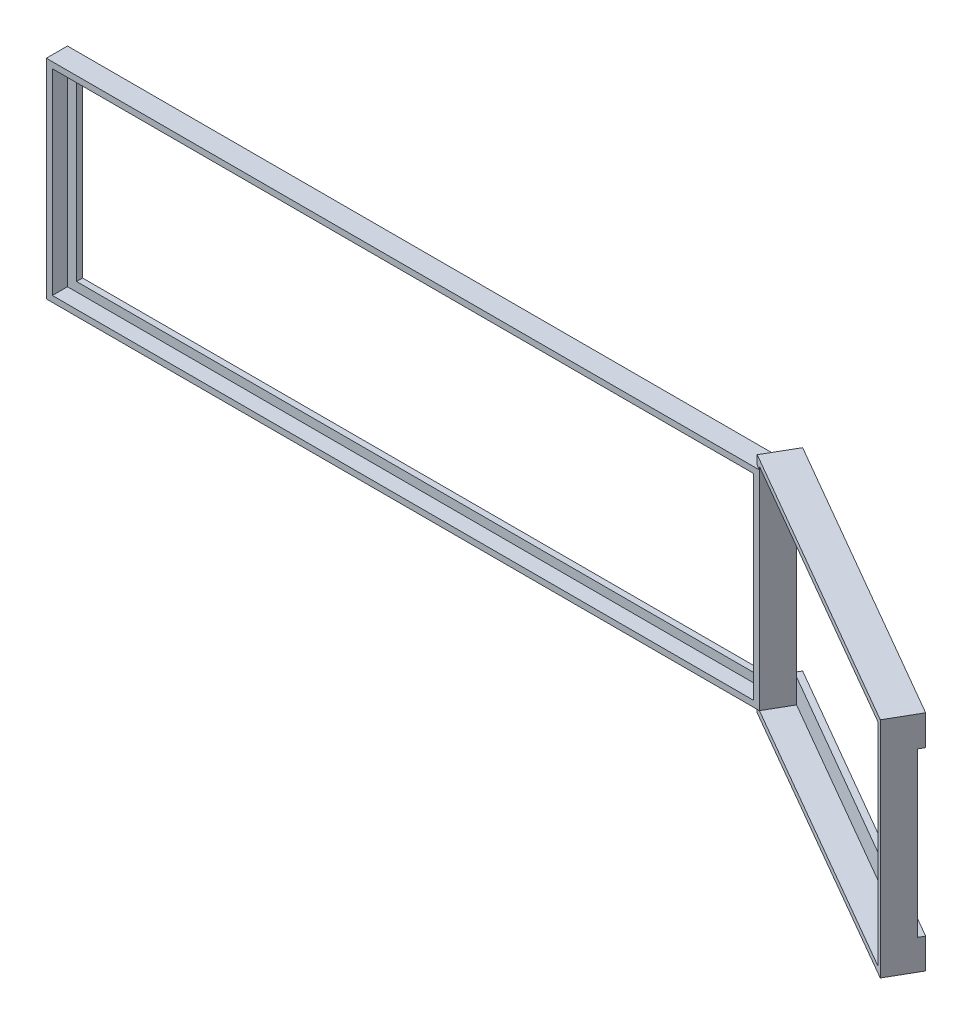
SolidWorks part; units mm, degrees
ref_plane "Front Plane" through (0, 0, 0) normal (0, 0, 1) x (1, 0, 0)
ref_plane "Top Plane" through (0, 0, 0) normal (0, 1, 0) x (1, 0, 0)
ref_plane "Right Plane" through (0, 0, 0) normal (1, 0, 0) x (0, 0, -1)
sketch "Sketch1" plane through (0, 0, 0) normal (0, 0, 1) x (1, 0, 0)
  line L0 (-118, 34.5) -> (-118, -34.5)
  line L1 (-116, 32.5) -> (116, 32.5)
  line L2 (-116, 32.5) -> (-116, -32.5)
  line L3 (-116, -32.5) -> (116, -32.5)
  line L4 (116, 32.5) -> (116, -32.5)
  line L5 (-116, 32.5) -> (116, -32.5) construction
  line L6 (-116, -32.5) -> (116, 32.5) construction
  line L7 (-118, -34.5) -> (118, -34.5)
  line L8 (118, 34.5) -> (118, -34.5)
  line L9 (-118, 34.5) -> (118, 34.5)
  point P0 (0, 0)
  dimension "D1" = 232
  dimension "D2" = 65
  dimension "D3" = 2
extrude "Display outline" add sketch "Sketch1" along normal blind 5
sketch "Sketch3" plane through (0, 0, 0) normal (0, 0, -1) x (-1, 0, 0)
  line L0 (113, 29.5) -> (-113, 29.5)
  line L1 (-113, 29.5) -> (-113, -29.5)
  line L2 (-113, -29.5) -> (113, -29.5)
  line L3 (113, -29.5) -> (113, 29.5)
  line L4 (118, 34.5) -> (-118, 34.5)
  line L5 (-118, 34.5) -> (-118, -34.5)
  line L6 (-118, -34.5) -> (118, -34.5)
  line L7 (118, -34.5) -> (118, 34.5)
  line L8 (118, 34.5) -> (-118, 34.5)
  line L9 (-118, 34.5) -> (-118, -34.5)
  line L10 (-118, -34.5) -> (118, -34.5)
  line L11 (118, -34.5) -> (118, 34.5)
  dimension "D1" = 0
  dimension "D2" = 5
extrude "Rear display retainer" add sketch "Sketch3" along normal blind 2
ref_plane "Stream deck plane" through (27.3349, 0, -47.3455) normal (-0.5, 0, 0.866) x (0, 1, 0)
sketch "Sketch2" plane through (27.3349, 0, -47.3455) normal (-0.5, 0, 0.866) x (0, 1, 0)
  line L0 (-36.5, -102.691) -> (-36.5, -213.941)
  line L1 (-34.5, -104.691) -> (35.5, -104.691)
  line L2 (-34.5, -104.691) -> (-34.5, -211.941)
  line L3 (-34.5, -211.941) -> (35.5, -211.941)
  line L4 (35.5, -104.691) -> (35.5, -211.941)
  line L5 (-36.5, -213.941) -> (37.5, -213.941)
  line L6 (37.5, -102.691) -> (37.5, -213.941)
  line L7 (-36.5, -102.691) -> (37.5, -102.691)
  dimension "D1" = 70
  dimension "D2" = 107.25
  dimension "D3" = 2
extrude "Stream deck outline" add sketch "Sketch2" against normal blind 9
sketch "Sketch4" plane through (31.8349, 0, -55.1397) normal (0.5, 0, -0.866) x (-0.866, 0, -0.5)
  line L0 (-213.941, 27.5) -> (-205.941, 27.5)
  line L1 (-203.941, 29.5) -> (-203.941, 32.5)
  line L2 (-201.941, 34.5) -> (-179.941, 34.5)
  line L3 (-177.941, 32.5) -> (-177.941, 29.5)
  line L4 (-102.691, -36.5) -> (-102.691, 37.5)
  line L5 (-102.691, 37.5) -> (-213.941, 37.5)
  line L6 (-213.941, 37.5) -> (-213.941, -36.5)
  line L7 (-213.941, -36.5) -> (-102.691, -36.5)
  line L8 (-102.691, -36.5) -> (-102.691, -26.5)
  line L9 (-102.691, 37.5) -> (-213.941, 37.5)
  line L10 (-213.941, 37.5) -> (-213.941, 27.5)
  line L11 (-213.941, -36.5) -> (-102.691, -36.5)
  line L12 (-175.941, 27.5) -> (-102.691, 27.5)
  line L13 (-213.941, -26.5) -> (-196.941, -26.5)
  line L14 (-194.941, -28.5) -> (-194.941, -31.5)
  line L15 (-192.941, -33.5) -> (-187.941, -33.5)
  line L16 (-185.941, -31.5) -> (-185.941, -28.5)
  line L17 (-183.941, -26.5) -> (-102.691, -26.5)
  line L18 (-213.941, -26.5) -> (-213.941, -36.5)
  line L19 (-102.691, 27.5) -> (-102.691, 37.5)
  line L20 (-211.941, 35.5) -> (-104.691, 35.5) construction
  line L21 (-211.941, -34.5) -> (-211.941, 35.5) construction
  line L22 (-104.691, -34.5) -> (-211.941, -34.5) construction
  arc A0 (-185.941, -28.5) -> (-183.941, -26.5) centre (-183.941, -28.5) cw
  arc A1 (-187.941, -33.5) -> (-185.941, -31.5) centre (-187.941, -31.5) ccw
  arc A2 (-194.941, -31.5) -> (-192.941, -33.5) centre (-192.941, -31.5) ccw
  arc A3 (-196.941, -26.5) -> (-194.941, -28.5) centre (-196.941, -28.5) cw
  arc A4 (-205.941, 27.5) -> (-203.941, 29.5) centre (-205.941, 29.5) ccw
  arc A5 (-177.941, 29.5) -> (-175.941, 27.5) centre (-175.941, 29.5) ccw
  arc A6 (-179.941, 34.5) -> (-177.941, 32.5) centre (-179.941, 32.5) cw
  arc A7 (-203.941, 32.5) -> (-201.941, 34.5) centre (-201.941, 32.5) cw
  point P36 (-201.941, 34.037)
  dimension "D2" = 2
  dimension "D3" = 8
  dimension "D4" = 8
  dimension "D5" = 34
  dimension "D6" = 7
  dimension "D7" = 8
  dimension "D8" = 7
  dimension "D9" = 17
  dimension "D10" = 26
  dimension "D1" = 0
extrude "Stream deck retainer" add sketch "Sketch4" along normal blind 2
